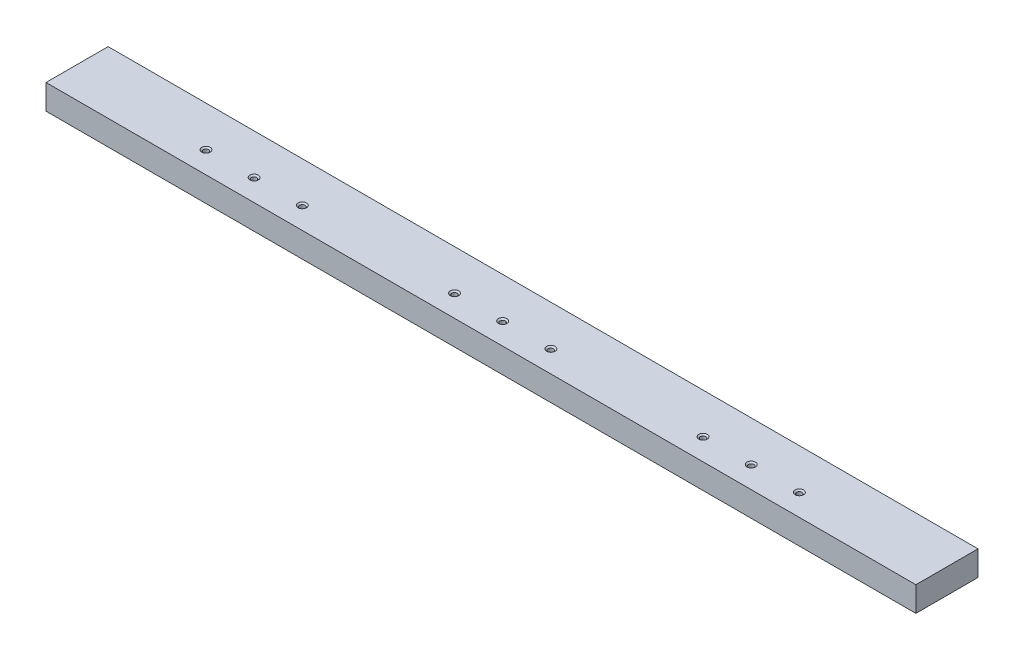
SolidWorks part; units mm, degrees
ref_plane "Front Plane" through (0, 0, 0) normal (0, 0, 1) x (1, 0, 0)
ref_plane "Top Plane" through (0, 0, 0) normal (0, 1, 0) x (1, 0, 0)
ref_plane "Right Plane" through (0, 0, 0) normal (1, 0, 0) x (0, 0, -1)
other "Bounding Box"
ref_plane "Default Plane" through (-280, 8, -20) normal (0, 0, 1) x (1, 0, 0)
sketch "Sketch1" plane through (0, 0, 0) normal (0, 1, 0) x (1, 0, 0)
  line L1 (-280, -20) -> (280, -20)
  line L2 (-280, -20) -> (-280, 20)
  line L3 (-280, 20) -> (280, 20)
  line L4 (280, -20) -> (280, 20)
  line L5 (-280, -20) -> (280, 20) construction
  line L6 (-280, 20) -> (280, -20) construction
  point P0 (0, 0)
  dimension "D1" = 560
  dimension "D2" = 40
extrude "Boss-Extrude1" add sketch "Sketch1" along normal mid plane 16
hole_wizard "#8-36 Tapped Hole1" positions "Sketch2" profile "Sketch4" tap size "#8-36" standard "ANSI Inch" end condition through all
sketch "Sketch2" plane through (0, 8, 0) normal (0, 1, 0) x (1, 0, 0)
  line L0 (129, -6) -> (191, -6) construction
  line L2 (-280, -20) -> (280, -20) construction
  line L3 (280, -20) -> (280, 20) construction
  point P1 (191, -6)
  point P3 (160, -6)
  point P5 (129, -6)
  dimension "D1" = 14
  dimension "D2" = 89
  dimension "D3" = 62
cosmetic thread "Hole Thread1" parameters "D2"=4.1656
cosmetic thread "Hole Thread2" parameters "D2"=4.1656
cosmetic thread "Hole Thread3" parameters "D2"=4.1656
sketch "Sketch4" plane through (191, 8, 6) normal (1, 0, 0) x (0, 0, 1)
  line L0 (0, 0) -> (0, 16)
  line L1 (0, 16) -> (1.7272, 16)
  line L2 (1.7272, 16) -> (1.7272, 0.8312)
  line L3 (1.7272, 0.8312) -> (2.7178, 0)
  line L5 (2.7178, 0) -> (0, 0)
  line L6 (-1.7272, 0.8312) -> (-2.7178, 0) construction
  line L11 (0, -6.35) -> (0, 107.95) construction
  dimension "Thru Tap Drill Dia." = 3.4544
  dimension "Thru Tap Drill Depth" = 16
  dimension "Near C'Sink Dia." = 5.4356
  dimension "Near C'Sink Angle" = 100
pattern_linear "LPattern1" count 3 spacing 160 along (-1, 0, 0) of "#8-36 Tapped Hole1"
cosmetic thread "Hole Thread4" parameters "D2"=4.1656
cosmetic thread "Hole Thread5" parameters "D2"=4.1656
cosmetic thread "Hole Thread6" parameters "D2"=4.1656
cosmetic thread "Hole Thread7" parameters "D2"=4.1656
cosmetic thread "Hole Thread8" parameters "D2"=4.1656
cosmetic thread "Hole Thread9" parameters "D2"=4.1656
